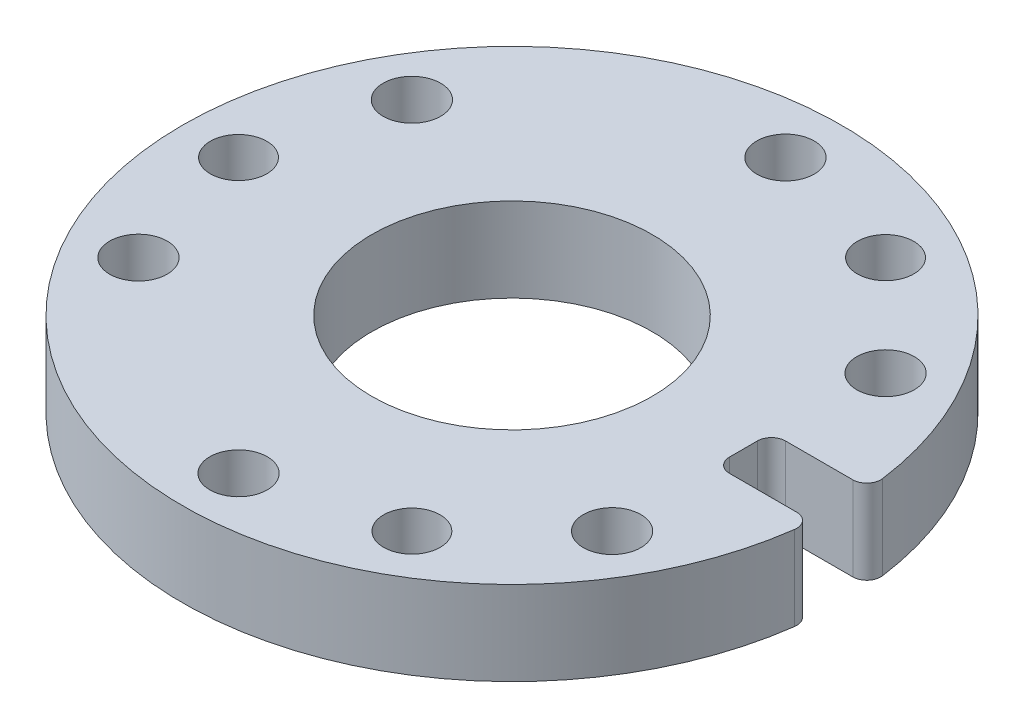
SolidWorks part; units mm, degrees
material "6061 合金"
ref_plane "前视基准面" through (0, 0, 0) normal (0, 0, 1) x (1, 0, 0)
ref_plane "上视基准面" through (0, 0, 0) normal (0, 1, 0) x (1, 0, 0)
ref_plane "右视基准面" through (0, 0, 0) normal (1, 0, 0) x (0, 0, -1)
sketch "草图1" plane through (0, 0, 0) normal (0, 1, 0) x (1, 0, 0)
  circle A0 centre (0, 0) radius 23.5
  circle A1 centre (0, 0) radius 10
  circle A2 centre (0, 0) radius 19.5 construction
  circle A3 centre (0, 19.5) radius 2.05
  circle A4 centre (16.8875, 9.75) radius 2.05
  circle A5 centre (16.8875, -9.75) radius 2.05
  circle A6 centre (0, -19.5) radius 2.05
  circle A7 centre (-16.8875, -9.75) radius 2.05
  circle A8 centre (-16.8875, 9.75) radius 2.05
  circle A9 centre (-19.5, 0) radius 2.015
  circle A10 centre (9.75, 16.8875) radius 2.015
  circle A11 centre (9.75, -16.8875) radius 2.015
  dimension "D1" = 47
  dimension "D2" = 20
  dimension "D3" = 39
  dimension "D4" = 4.1
  dimension "D6" = 4.03
  dimension "D7" = 3
  dimension "D5" = 6
extrude "凸台-拉伸1" add sketch "草图1" along normal blind 6
sketch "草图2" plane through (0, 6, 0) normal (0, 1, 0) x (1, 0, 0)
  line L0 (0, 0) -> (23.5, 0) construction
  line L2 (16.5, 2) -> (28.7401, 2)
  line L3 (16.5, 2) -> (16.5, -2)
  line L4 (16.5, -2) -> (28.7401, -2)
  line L5 (28.7401, 2) -> (28.7401, -2)
  circle A0 centre (0, 0) radius 23.5 construction
  dimension "D1" = 7
  dimension "D2" = 2
extrude "切除-拉伸1" cut sketch "草图2" against normal blind 10
fillet "圆角1" radius 1 4 edges at (23.4147, 3, 2) (23.4147, 3, -2) (16.5, 3, 2) (16.5, 3, -2)
